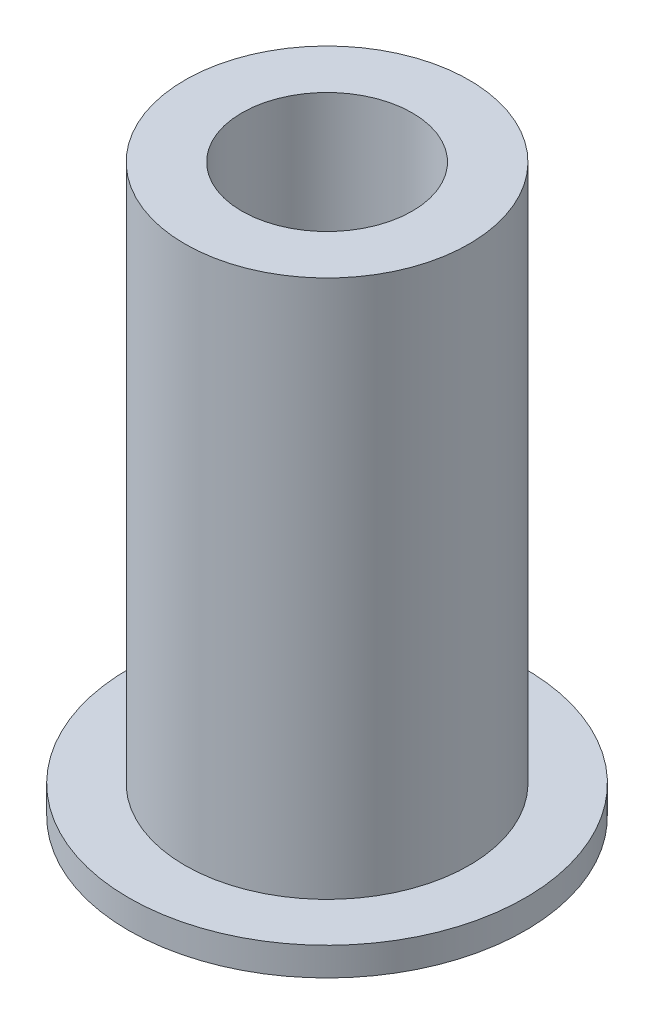
SolidWorks part; units mm, degrees
material "Brass"
ref_plane "Front" through (0, 0, 0) normal (0, 0, 1) x (1, 0, 0)
ref_plane "Top" through (0, 0, 0) normal (0, 1, 0) x (1, 0, 0)
ref_plane "Right" through (0, 0, 0) normal (1, 0, 0) x (0, 0, -1)
sketch "Sketch1" plane through (0, 0, 0) normal (0, 1, 0) x (1, 0, 0)
  circle A0 centre (0, 0) radius 4.7752
  circle A1 centre (0, 0) radius 7.9629
  circle A2 centre (0, 0) radius 11.1125
  dimension "ID" = 9.5504
  dimension "OD" = 15.9258
  dimension "FlangeOD" = 22.225
sketch "Sketch2" plane through (0, 0, 0) normal (0, 1, 0) x (1, 0, 0)
  circle A0 centre (0, 0) radius 4.7752 construction
  circle A1 centre (0, 0) radius 7.9629 construction
  circle A2 centre (0, 0) radius 4.7752
  circle A3 centre (0, 0) radius 7.9629
extrude "Boss-Extrude1" add sketch "Sketch2" along normal blind 31.75
sketch "Sketch3" plane through (0, 0, 0) normal (0, 1, 0) x (1, 0, 0)
  circle A0 centre (0, 0) radius 11.1125 construction
  circle A1 centre (0, 0) radius 7.9629 construction
  circle A2 centre (0, 0) radius 11.1125
  circle A3 centre (0, 0) radius 7.9629
extrude "Boss-Extrude2" add sketch "Sketch3" along normal blind 1.5875
